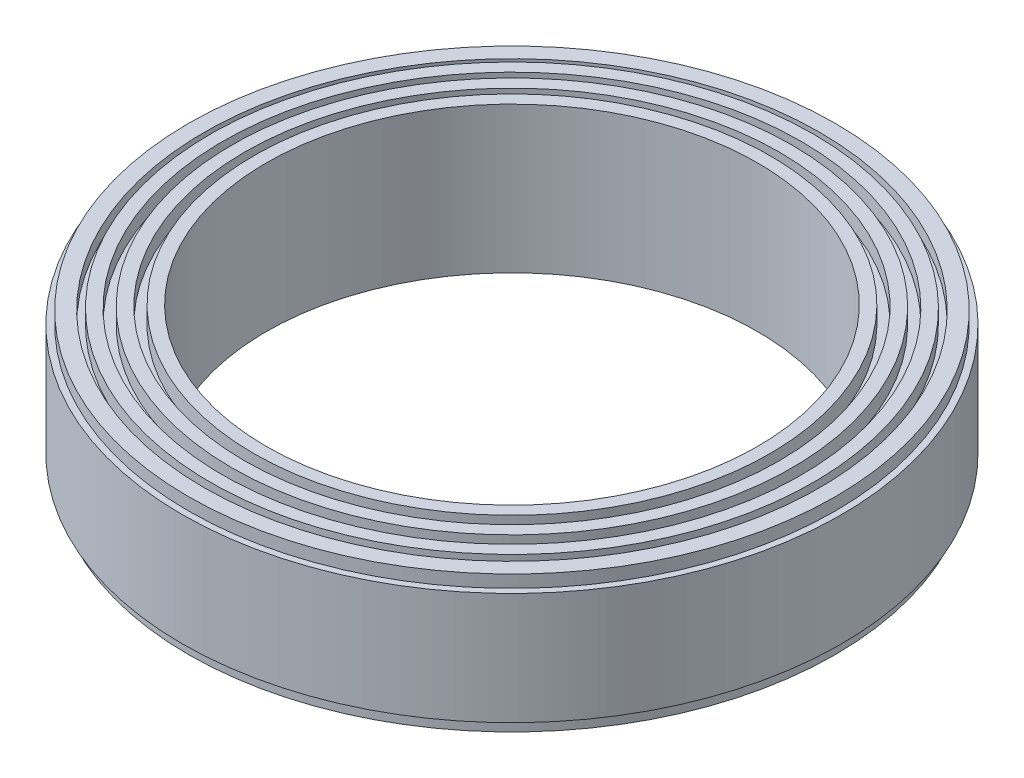
SolidWorks part; units mm, degrees
ref_plane "Front Plane" through (0, 0, 0) normal (0, 0, 1) x (1, 0, 0)
ref_plane "Top Plane" through (0, 0, 0) normal (0, 1, 0) x (1, 0, 0)
ref_plane "Right Plane" through (0, 0, 0) normal (1, 0, 0) x (0, 0, -1)
sketch "Sketch1" plane through (0, 0, 0) normal (0, 1, 0) x (1, 0, 0)
  circle A0 centre (0, 0) radius 106
  circle A1 centre (0, 0) radius 80
extrude "Presentation tire casing annulus" add sketch "Sketch1" along normal mid plane 36
sketch "Sketch2" plane through (0, 0, 0) normal (0, 1, 0) x (1, 0, 0)
  circle A0 centre (0, 0) radius 104
  circle A1 centre (0, 0) radius 99
extrude "outer tire shoulder line" add sketch "Sketch2" along normal mid plane 44
sketch "Sketch3" plane through (0, 0, 0) normal (0, 1, 0) x (1, 0, 0)
  circle A0 centre (0, 0) radius 97
  circle A1 centre (0, 0) radius 93
extrude "outer tread groove line" add sketch "Sketch3" along normal mid plane 45
sketch "Sketch4" plane through (0, 0, 0) normal (0, 1, 0) x (1, 0, 0)
  circle A0 centre (0, 0) radius 90
  circle A1 centre (0, 0) radius 86
extrude "inner tread groove line" add sketch "Sketch4" along normal mid plane 46
sketch "Sketch5" plane through (0, 0, 0) normal (0, 1, 0) x (1, 0, 0)
  circle A0 centre (0, 0) radius 83
  circle A1 centre (0, 0) radius 79
extrude "inner tire bead line" add sketch "Sketch5" along normal mid plane 47
